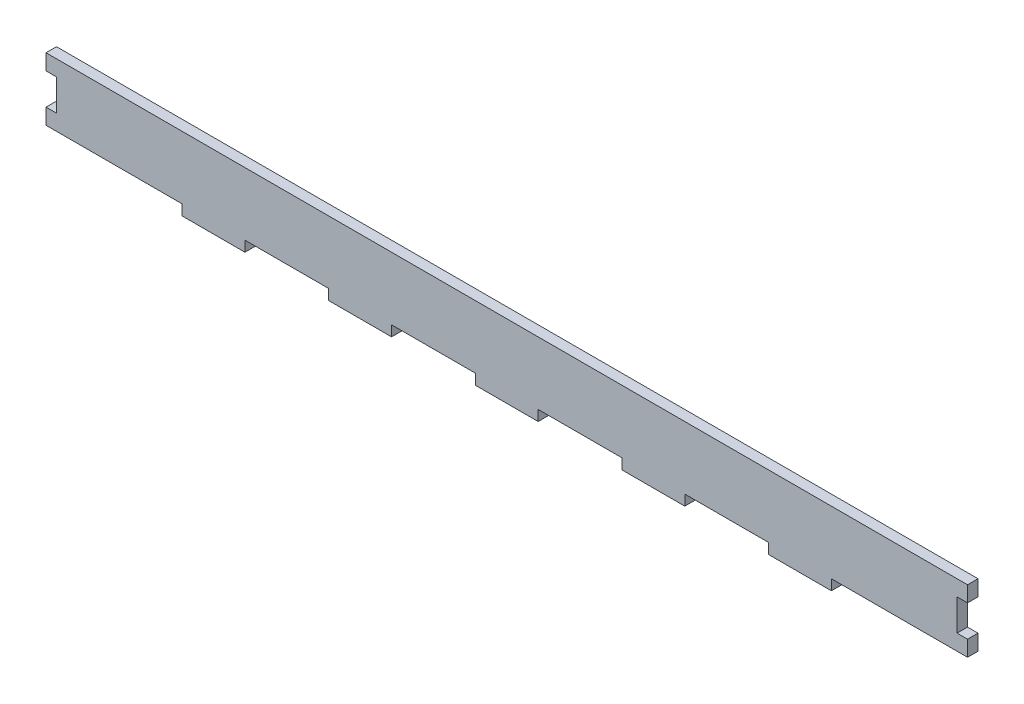
SolidWorks part; units mm, degrees
ref_plane "Front Plane" through (0, 0, 0) normal (0, 0, 1) x (1, 0, 0)
ref_plane "Top Plane" through (0, 0, 0) normal (0, 1, 0) x (1, 0, 0)
ref_plane "Right Plane" through (0, 0, 0) normal (1, 0, 0) x (0, 0, -1)
sketch "Sketch1" plane through (0, 0, 0) normal (0, 0, 1) x (1, 0, 0)
  line L0 (225, -390) -> (225, -352.4381) construction
  line L5 (210, -430) -> (170, -430)
  line L7 (240, -430) -> (240, -435)
  line L8 (240, -435) -> (210, -435)
  line L9 (210, -430) -> (210, -435)
  line L10 (225, -430) -> (210, -435) construction
  line L11 (240, -435) -> (225, -430) construction
  line L12 (170, -430) -> (170, -435)
  line L13 (170, -435) -> (140, -435)
  line L14 (140, -430) -> (140, -435)
  line L15 (100, -430) -> (100, -435)
  line L16 (100, -435) -> (70, -435)
  line L17 (70, -430) -> (70, -435)
  line L18 (240, -430) -> (240, -435)
  line L19 (240, -435) -> (210, -435)
  line L20 (210, -430) -> (210, -435)
  line L21 (170, -430) -> (170, -435)
  line L22 (170, -435) -> (140, -435)
  line L23 (140, -430) -> (140, -435)
  line L24 (310, -430) -> (310, -435)
  line L25 (310, -435) -> (280, -435)
  line L26 (280, -430) -> (280, -435)
  line L27 (240, -430) -> (240, -435)
  line L28 (240, -435) -> (210, -435)
  line L29 (210, -430) -> (210, -435)
  line L30 (310, -430) -> (310, -435)
  line L31 (310, -435) -> (280, -435)
  line L32 (280, -430) -> (280, -435)
  line L33 (380, -430) -> (380, -435)
  line L34 (380, -435) -> (350, -435)
  line L35 (350, -430) -> (350, -435)
  line L36 (280, -430) -> (240, -430)
  line L37 (350, -430) -> (310, -430)
  line L38 (140, -430) -> (100, -430)
  line L39 (445, 605) -> (445, -407.5) construction
  line L41 (440.0003, -422.5) -> (445, -422.5)
  line L43 (440.0003, -407.5) -> (445, -407.5)
  line L45 (440.0003, -400) -> (445, -400)
  line L46 (445, -400) -> (445, -407.5)
  line L47 (440.0003, -430) -> (380, -430)
  line L48 (70, -430) -> (9.9997, -430)
  line L50 (9.9997, -407.5) -> (5, -407.5)
  line L51 (9.9997, -422.5) -> (5, -422.5)
  line L53 (9.9997, -400) -> (440.0003, -400)
  line L54 (445, -422.5) -> (445, -430)
  line L55 (445, -430) -> (440.0003, -430)
  line L56 (445, -422.5) -> (445, -1428.3396) construction
  line L57 (440.0003, -422.5) -> (440.0003, -407.5)
  line L58 (9.9997, -400) -> (5, -400)
  line L59 (5, -400) -> (5, -407.5)
  line L60 (9.9997, -430) -> (5, -430)
  line L61 (5, -430) -> (5, -422.5)
  line L62 (9.9997, -422.5) -> (9.9997, -407.5)
  point P7 (225, -430)
  point P9 (440.0003, -410)
  point P49 (9.9997, -410)
  dimension "D1" = 30
  dimension "D2" = 7.5
  dimension "D3" = 30
  dimension "D4" = 7.5
  dimension "D7" = 15
  dimension "D8" = 4.9997
  dimension "D5" = 3
  dimension "D6" = 3
extrude "Boss-Extrude1" add sketch "Sketch1" against normal blind 5
